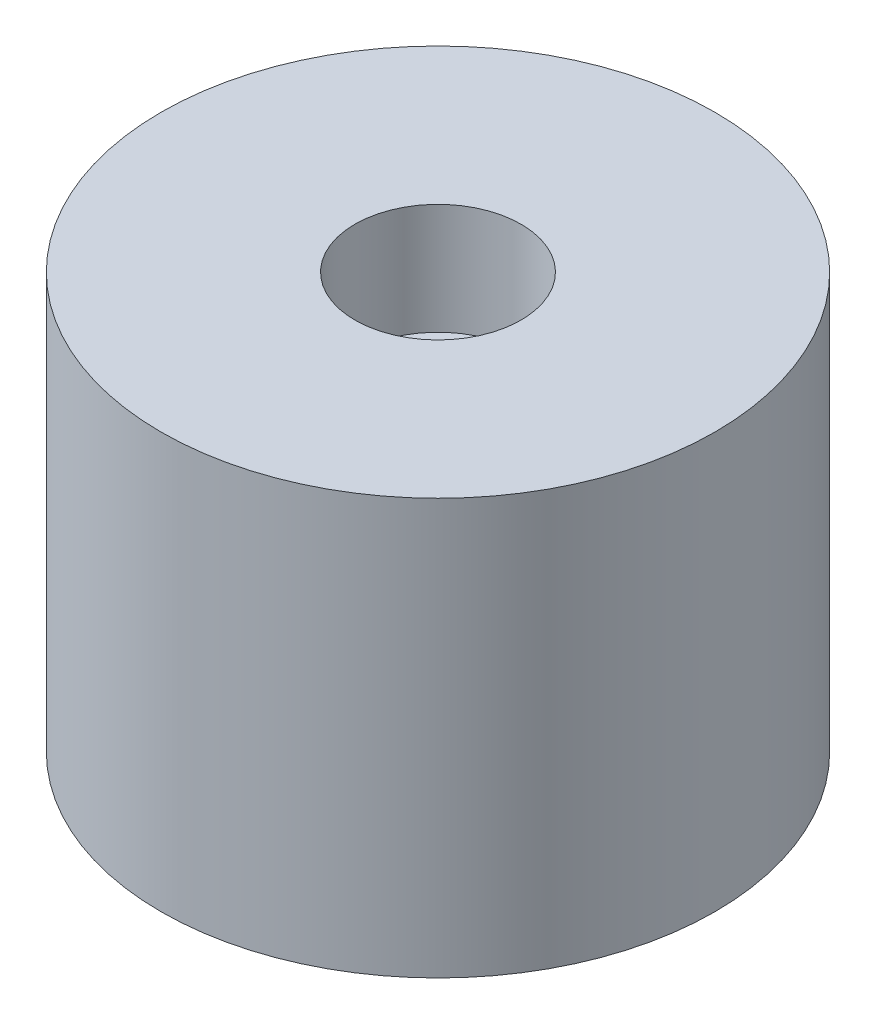
SolidWorks part; units mm, degrees
ref_plane "前视基准面" through (0, 0, 0) normal (0, 0, 1) x (1, 0, 0)
ref_plane "上视基准面" through (0, 0, 0) normal (0, 1, 0) x (1, 0, 0)
ref_plane "右视基准面" through (0, 0, 0) normal (1, 0, 0) x (0, 0, -1)
other "Configuration Table"
sketch "草图1" plane through (0, 0, 0) normal (0, 0, 1) x (1, 0, 0)
  line L0 (0, 0) -> (10, 0) construction
  line L1 (10, -7.5) -> (10, 7.5)
  line L2 (10, 7.5) -> (3, 7.5)
  line L3 (3, 7.5) -> (3, 3.5)
  line L4 (3, 3.5) -> (0, 3.5)
  line L5 (0, 3.5) -> (0, -3.5)
  line L6 (3, -3.5) -> (0, -3.5)
  line L7 (3, -7.5) -> (3, -3.5)
  line L8 (10, -7.5) -> (3, -7.5)
  line L9 (10, 7.5) -> (3, 7.5)
  line L10 (3, 7.5) -> (3, 3.5)
  line L11 (3, 3.5) -> (0, 3.5)
  line L12 (3, -3.5) -> (0, -3.5)
  line L13 (3, -7.5) -> (3, -3.5)
  line L14 (10, -7.5) -> (3, -7.5)
  line L15 (10, 7.5) -> (3, 7.5)
  line L16 (3, 7.5) -> (3, 3.5)
  line L17 (3, 3.5) -> (0, 3.5)
  line L18 (3, -3.5) -> (0, -3.5)
  line L19 (3, -7.5) -> (3, -3.5)
  line L20 (10, -7.5) -> (3, -7.5)
  line L21 (10, 7.5) -> (3, 7.5)
  line L22 (3, 7.5) -> (3, 3.5)
  line L23 (3, 3.5) -> (0, 3.5)
  line L24 (3, -3.5) -> (0, -3.5)
  line L25 (3, -7.5) -> (3, -3.5)
  line L26 (10, -7.5) -> (3, -7.5)
  dimension "D1" = 10
  dimension "D2" = 15
  dimension "D3" = 3
  dimension "D4" = 4
revolve "旋转3" add sketch "草图1" angle 360 about L5
